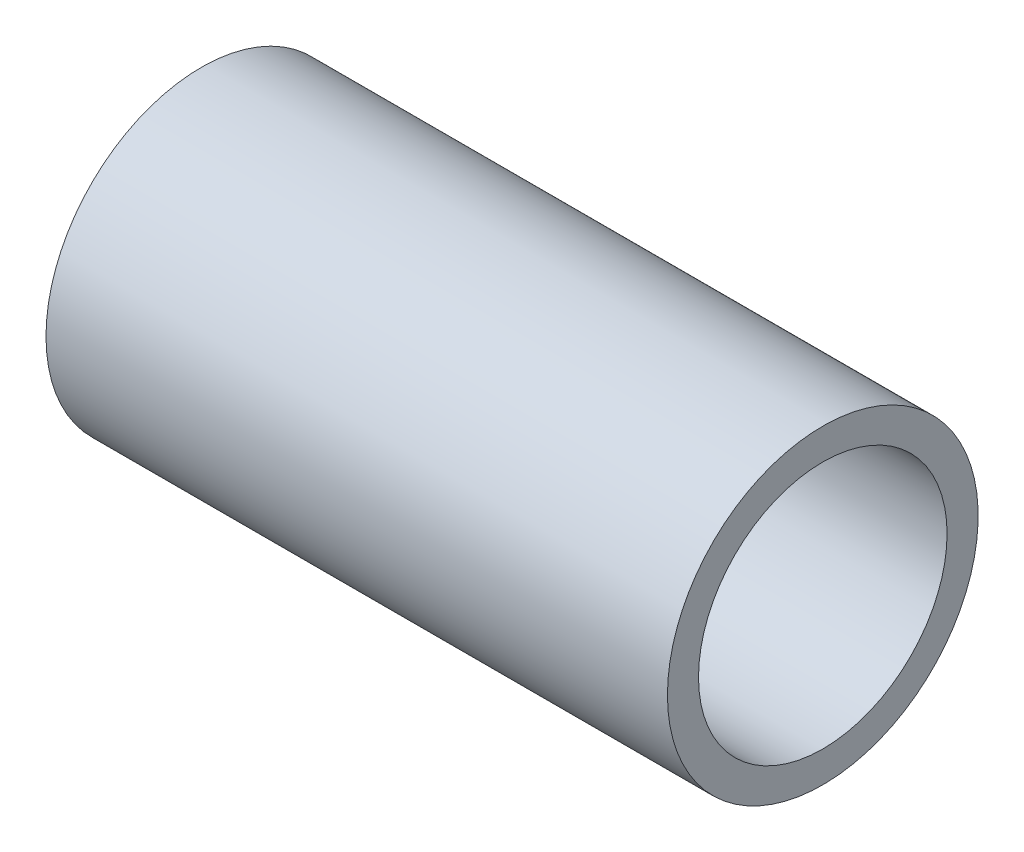
SolidWorks part; units mm, degrees
ref_plane "Ebene vorne" through (0, 0, 0) normal (0, 0, 1) x (1, 0, 0)
ref_plane "Ebene oben" through (0, 0, 0) normal (0, 1, 0) x (1, 0, 0)
ref_plane "Ebene rechts" through (0, 0, 0) normal (1, 0, 0) x (0, 0, -1)
sketch "Skizze1" plane through (0, 0, 0) normal (0, 0, 1) x (1, 0, 0)
  line L0 (0, 0) -> (200, 0) construction
  line L1 (0, 50) -> (0, 32.5)
  line L2 (0, 32.5) -> (5, 32.5)
  line L3 (30, 32.5) -> (30, 40)
  line L4 (30, 40) -> (200, 40)
  line L5 (200, 40) -> (200, 50)
  line L6 (200, 50) -> (0, 50)
  line L7 (0, 0) -> (0, 32.5) construction
  line L8 (200, 40) -> (200, 0) construction
  line L9 (5, 32.5) -> (5, 34.7)
  line L10 (5, 34.7) -> (8, 34.7)
  line L11 (8, 34.7) -> (8, 32.5)
  line L12 (20, 32.5) -> (20, 34.7)
  line L13 (20, 34.7) -> (23, 34.7)
  line L14 (23, 34.7) -> (23, 32.5)
  line L15 (8, 32.5) -> (20, 32.5)
  line L16 (23, 32.5) -> (30, 32.5)
  point P15 (5, 33.6)
  dimension "D1" = 65
  dimension "D2" = 100
  dimension "D3" = 200
  dimension "D4" = 30
  dimension "D5" = 80
  dimension "D6" = 3
  dimension "D7" = 3
  dimension "D8" = 2.2
  dimension "D9" = 5
  dimension "D10" = 20
revolve "Rotation1" add sketch "Skizze1" angle 360 about L0
